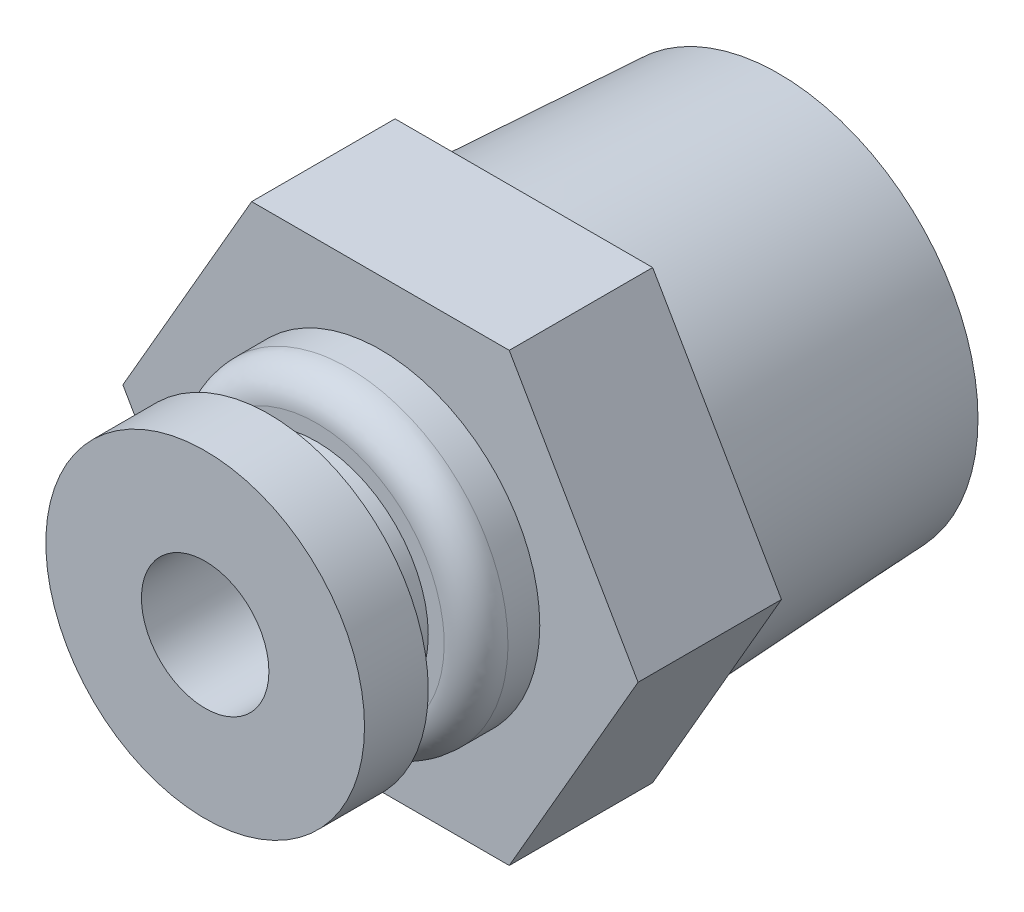
SolidWorks part; units mm, degrees
ref_plane "Front Plane" through (0, 0, 0) normal (0, 0, 1) x (1, 0, 0)
ref_plane "Top Plane" through (0, 0, 0) normal (0, 1, 0) x (1, 0, 0)
ref_plane "Right Plane" through (0, 0, 0) normal (1, 0, 0) x (0, 0, -1)
sketch "Sketch1" plane through (0, 0, 0) normal (0, 0, 1) x (1, 0, 0)
  circle A0 centre (0, 0) radius 6.25
  dimension "D1" = 12.5
extrude "Boss-Extrude1" add sketch "Sketch1" along normal blind 8 draft 3 draft outward yes
sketch "Sketch2" plane through (0, 0, 8) normal (0, 0, 1) x (1, 0, 0)
  line L1 (8.0829, 0) -> (4.0415, 7)
  line L2 (4.0415, 7) -> (-4.0415, 7)
  line L3 (-4.0415, 7) -> (-8.0829, 0)
  line L4 (-8.0829, 0) -> (-4.0415, -7)
  line L5 (-4.0415, -7) -> (4.0415, -7)
  line L6 (4.0415, -7) -> (8.0829, 0)
  circle A0 centre (0, 0) radius 7 construction
  dimension "D1" = 14
extrude "Boss-Extrude2" add sketch "Sketch2" along normal blind 4.5
sketch "Sketch3" plane through (0, 0, 12.5) normal (0, 0, 1) x (1, 0, 0)
  circle A0 centre (0, 0) radius 5
  dimension "D1" = 10
extrude "Boss-Extrude3" add sketch "Sketch3" along normal blind 2
sketch "Sketch9" plane through (0, 0, 14.5) normal (0, 0, 1) x (1, 0, 0)
  circle A0 centre (0, 0) radius 3.5
  dimension "D1" = 7
extrude "Boss-Extrude6" add sketch "Sketch9" along normal blind 0.5
fillet "Fillet1" radius 1 1 edges at (5, 0, 14.5)
sketch "Sketch4" plane through (0, 0, 15) normal (0, 0, 1) x (1, 0, 0)
  circle A0 centre (0, 0) radius 3
  dimension "D1" = 6
extrude "Boss-Extrude4" add sketch "Sketch4" along normal blind 1
sketch "Sketch5" plane through (0, 0, 16) normal (0, 0, 1) x (1, 0, 0)
  circle A0 centre (0, 0) radius 5
  dimension "D1" = 10
extrude "Boss-Extrude5" add sketch "Sketch5" along normal blind 2
sketch "Sketch6" plane through (0, 0, 18) normal (0, 0, 1) x (1, 0, 0)
  circle A0 centre (0, 0) radius 2
  dimension "D1" = 4
extrude "Cut-Extrude1" cut sketch "Sketch6" against normal offset from surface (9.5 mm away) 4 up to face at (5, 0, 12.5) offset beyond the face yes
sketch "Sketch7" plane through (0, 0, 8.5) normal (0, 0, 1) x (1, 0, 0)
  line L1 (0, -1.7321) -> (1.5, -0.866)
  line L2 (1.5, -0.866) -> (1.5, 0.866)
  line L3 (1.5, 0.866) -> (0, 1.7321)
  line L4 (0, 1.7321) -> (-1.5, 0.866)
  line L5 (-1.5, 0.866) -> (-1.5, -0.866)
  line L6 (-1.5, -0.866) -> (0, -1.7321)
  circle A0 centre (0, 0) radius 1.5 construction
  dimension "D1" = 3
extrude "Cut-Extrude2" cut sketch "Sketch7" against normal offset from surface (6.5 mm away) 6 up to face at (6.6693, 0, 8) offset beyond the face yes
sketch "Sketch8" plane through (0, 0, 0) normal (0, 0, -1) x (-1, 0, 0)
  circle A0 centre (0, 0) radius 4.5
  dimension "D1" = 9
extrude "Cut-Extrude3" cut sketch "Sketch8" against normal up to surface (2 mm away) up to face at (0, 0, 2)
